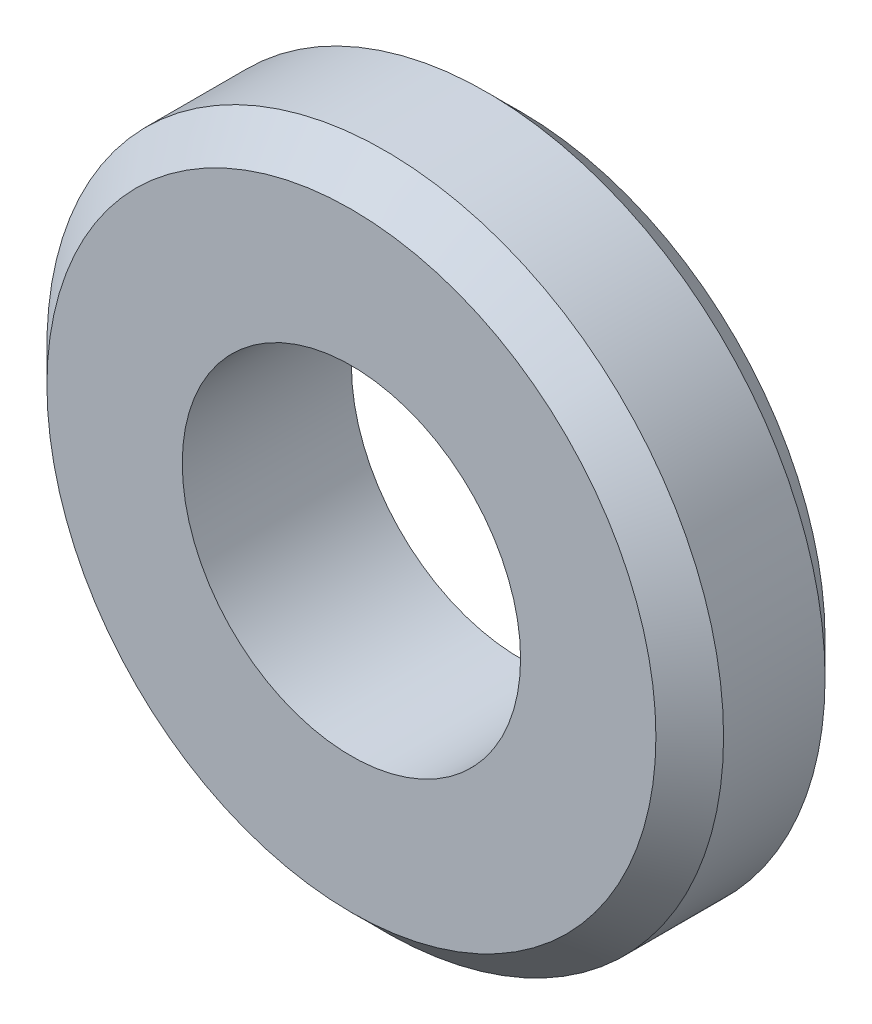
SolidWorks part; units mm, degrees
ref_plane "Front Plane" through (0, 0, 0) normal (0, 0, 1) x (1, 0, 0)
ref_plane "Top Plane" through (0, 0, 0) normal (0, 1, 0) x (1, 0, 0)
ref_plane "Right Plane" through (0, 0, 0) normal (1, 0, 0) x (0, 0, -1)
sketch "Sketch1" plane through (0, 0, 0) normal (0, 0, 1) x (1, 0, 0)
  circle A0 centre (0, 0) radius 1
  circle A1 centre (0, 0) radius 0.5
  dimension "D1" = 1
  dimension "D2" = 2
extrude "Boss-Extrude1" add sketch "Sketch1" along normal blind 0.5
chamfer "Chamfer1" distance 0.1 angle 45 2 edges at (1, 0, 0) (1, 0, 0.5)
scale "Scale1" scale about centroid uniform scaling yes scale factor 1.9329
scale "Scale2" scale about centroid uniform scaling yes scale factor 1.5
